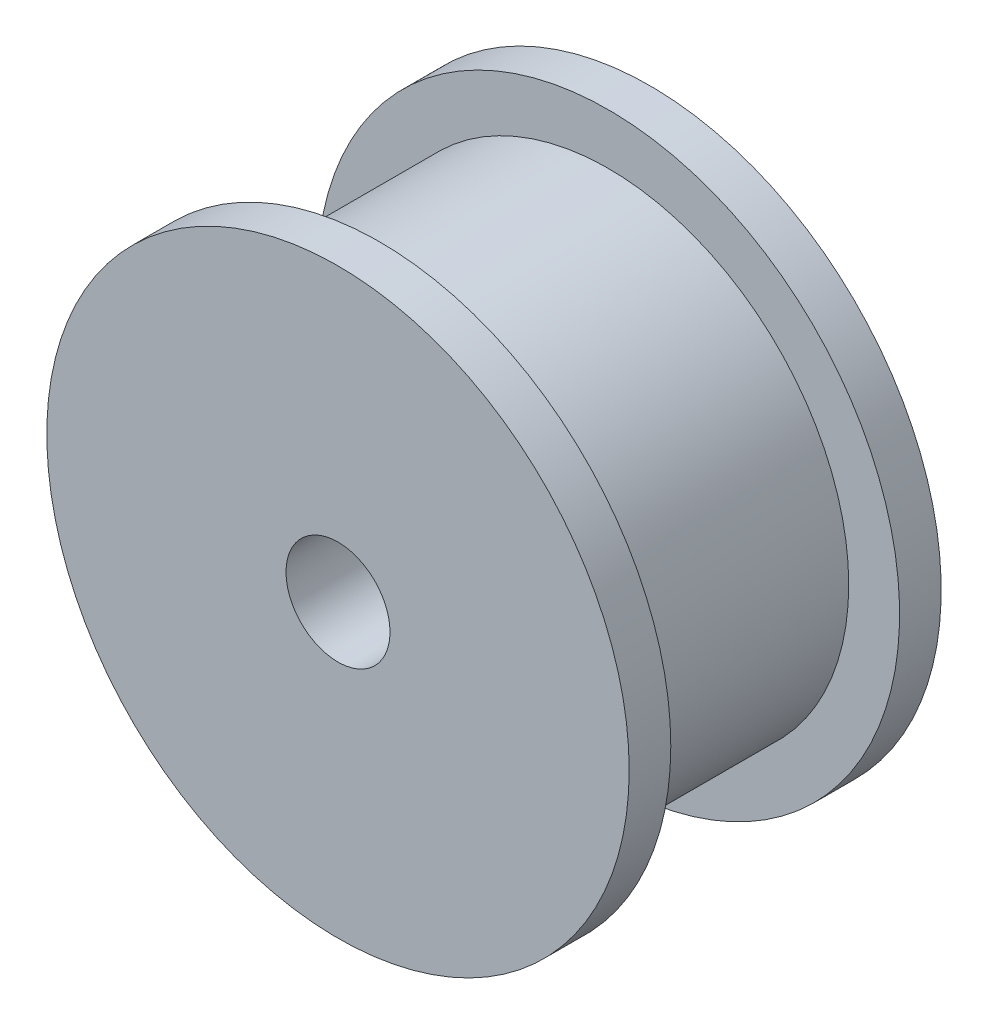
SolidWorks part; units mm, degrees
ref_plane "前视基准面" through (0, 0, 0) normal (0, 0, 1) x (1, 0, 0)
ref_plane "上视基准面" through (0, 0, 0) normal (0, 1, 0) x (1, 0, 0)
ref_plane "右视基准面" through (0, 0, 0) normal (1, 0, 0) x (0, 0, -1)
other "Configuration Table"
sketch "草图1" plane through (0, 0, 0) normal (0, 0, 1) x (1, 0, 0)
  circle A0 centre (0, 0) radius 11.555
  dimension "D1" = 23.11
extrude "凸台-拉伸1" add sketch "草图1" along normal blind 11
sketch "草图2" plane through (0, 0, 11) normal (0, 0, 1) x (1, 0, 0)
  circle A0 centre (0, 0) radius 14
  dimension "D1" = 28
extrude "凸台-拉伸2" add sketch "草图2" along normal blind 2
sketch "草图3" plane through (0, 0, 0) normal (0, 0, -1) x (-1, 0, 0)
  circle A1 centre (0, 0) radius 14 construction
  circle A2 centre (0, 0) radius 14
extrude "凸台-拉伸3" add sketch "草图3" along normal blind 2
sketch "草图4" plane through (0, 0, -2) normal (0, 0, -1) x (-1, 0, 0)
  circle A0 centre (0, 0) radius 2.5
  dimension "D1" = 5
extrude "切除-拉伸1" cut sketch "草图4" against normal through all
